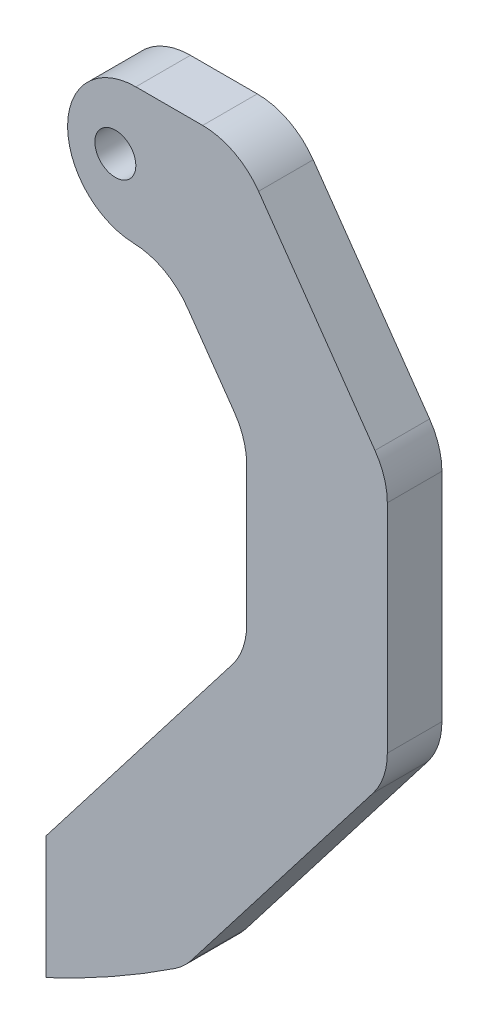
SolidWorks part; units mm, degrees
ref_plane "Front Plane" through (0, 0, 0) normal (0, 0, 1) x (1, 0, 0)
ref_plane "Top Plane" through (0, 0, 0) normal (0, 1, 0) x (1, 0, 0)
ref_plane "Right Plane" through (0, 0, 0) normal (1, 0, 0) x (0, 0, -1)
sketch "Sketch1" plane through (0, 0, 0) normal (0, 0, 1) x (1, 0, 0)
  line L0 (10.1476, -27.8732) -> (35.1476, -27.8732)
  line L5 (6.9976, -147.4931) -> (6.9976, -129.4931)
  line L6 (6.9976, -129.4931) -> (36.3889, -91.3861)
  line L9 (10.1476, -47.8732) -> (10.1476, -27.8732)
  line L10 (-3.1523, -37.8732) -> (17.1476, -37.8732) construction
  line L11 (6.9976, -37.8732) -> (6.9976, -147.4931) construction
  line L12 (56.9976, -97.4136) -> (27.2696, -135.9572)
  line L14 (10.1476, -47.8732) -> (24.7362, -47.8732)
  line L15 (35.1476, -27.8732) -> (56.9976, -59.0783)
  line L16 (-13.0023, -47.8732) -> (26.9977, -47.8732) construction
  line L17 (24.7362, -47.8732) -> (36.3889, -64.5149)
  line L18 (56.9976, -59.0783) -> (56.9976, -97.4136)
  line L19 (36.3889, -64.5149) -> (36.3889, -91.3861)
  arc A0 (6.9976, -147.4931) -> (27.2696, -135.9572) centre (-55.9725, -13.2558) ccw
  circle A1 centre (17.1476, -37.8732) radius 3
  dimension "D2" = 10
  dimension "D1" = 10
  dimension "D3" = 7
  dimension "D7" = 25
  dimension "D8" = 235
  dimension "D9" = 18
extrude "Boss-Extrude1" add sketch "Sketch1" along normal blind 8
fillet "Fillet1" radius 10 7 edges at (35.1476, -27.8732, 4) (56.9976, -59.0783, 4) (56.9976, -97.4136, 4) (27.2696, -135.9572, 4) (36.3889, -91.3861, 4) (36.3889, -64.5149, 4) (24.7362, -47.8732, 4)
fillet "Fillet2" radius 10 2 edges at (10.1476, -27.8732, 4) (10.1476, -47.8732, 4)
